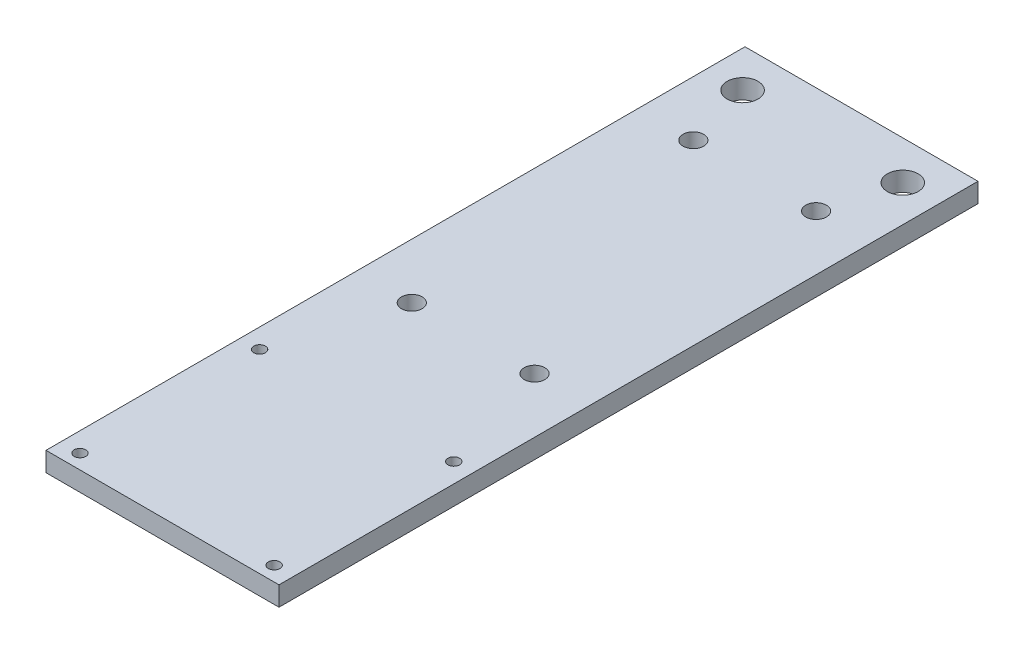
SolidWorks part; units mm, degrees
material "6061-T6 (SS)"
ref_plane "Front Plane" through (0, 0, 0) normal (0, 0, 1) x (1, 0, 0)
ref_plane "Top Plane" through (0, 0, 0) normal (0, 1, 0) x (1, 0, 0)
ref_plane "Right Plane" through (0, 0, 0) normal (1, 0, 0) x (0, 0, -1)
sketch "Plate sketch" plane through (0, 0, 0) normal (0, 1, 0) x (1, 0, 0)
  line L1 (-38.1, -114.3) -> (38.1, -114.3)
  line L2 (-38.1, -114.3) -> (-38.1, 114.3)
  line L3 (-38.1, 114.3) -> (38.1, 114.3)
  line L4 (38.1, -114.3) -> (38.1, 114.3)
  line L5 (-38.1, -114.3) -> (38.1, 114.3) construction
  line L6 (-38.1, 114.3) -> (38.1, -114.3) construction
  point P0 (0, 0)
  dimension "D1" = 228.6
  dimension "D2" = 76.2
extrude "Plate extrude" add sketch "Plate sketch" along normal blind 6.35
hole_wizard "1/4 Clearance Hole2" positions "Sketch4" profile "Sketch5" hole size "1/4" standard "ANSI Inch" end condition through all
sketch "Sketch4" plane through (0, 6.35, 0) normal (0, 1, 0) x (1, 0, 0)
  line L17 (-20.066, 79.375) -> (20.066, 79.375) construction
  line L18 (-20.066, 79.375) -> (-20.066, -12.7) construction
  line L19 (-20.066, -12.7) -> (20.066, -12.7) construction
  line L20 (20.066, 79.375) -> (20.066, -12.7) construction
  line L27 (-38.1, 114.3) -> (-38.1, -114.3) construction
  line L29 (38.1, 114.3) -> (-38.1, 114.3) construction
  point P155 (-20.066, 79.375)
  point P156 (20.066, -12.7)
  point P159 (-20.066, -12.7)
  point P160 (20.066, 79.375)
  dimension "D1" = 40.132
  dimension "D2" = 92.075
  dimension "D3" = 127
  dimension "D4" = 18.034
sketch "Sketch5" plane through (-20.066, 6.35, -79.375) normal (1, 0, 0) x (0, 0, 1)
  line L0 (0, 0) -> (0, 6.35)
  line L1 (0, 6.35) -> (3.3782, 6.35)
  line L2 (3.3782, 6.35) -> (3.3782, 0)
  line L5 (3.3782, 0) -> (0, 0)
  line L11 (0, -6.35) -> (0, 107.95) construction
  dimension "Thru Hole Dia." = 6.7564
  dimension "Thru Hole Depth" = 6.35
hole_wizard "#6 Clearance Hole1" positions "Sketch7" profile "Sketch8" hole size "#6" standard "ANSI Inch" end condition through all
sketch "Sketch7" plane through (0, 6.35, 0) normal (0, 1, 0) x (1, 0, 0)
  line L13 (0, -1000) -> (0, 49000) construction
  line L14 (-38.1, -114.3) -> (38.1, -114.3) construction
  line L18 (-31.75, -109.5375) -> (31.75, -109.5375) construction
  point P164 (-31.75, -50.8)
  point P166 (-31.75, -109.5375)
  point P210 (31.75, -50.8)
  point P212 (31.75, -109.5375)
  point P229 (0, -114.3)
  point P230 (0, -109.5375)
  point P237 (0, 0)
  dimension "D1" = 58.7375
  dimension "D3" = 63.5
  dimension "D6" = 4.7625
sketch "Sketch8" plane through (-31.75, 6.35, 50.8) normal (1, 0, 0) x (0, 0, 1)
  line L0 (0, 0) -> (0, 6.35)
  line L1 (0, 6.35) -> (1.8986, 6.35)
  line L2 (1.8986, 6.35) -> (1.8986, 0)
  line L5 (1.8986, 0) -> (0, 0)
  line L11 (0, -6.35) -> (0, 107.95) construction
  dimension "Thru Hole Dia." = 3.7973
  dimension "Thru Hole Depth" = 6.35
hole_wizard "Ø6.0mm Dowel Hole1" positions "Sketch9" profile "Sketch10" hole size "Ø6.0" standard "ANSI Metric"
sketch "Sketch9" plane through (0, 5, 0) normal (0, 1, 0) x (1, 0, 0)
  line L0 (40, 120) -> (-40, 120) construction
  line L3 (40, -120) -> (40, 120) construction
  line L4 (-40, 120) -> (-40, -120) construction
  point P0 (-34, 110)
  point P2 (34, 110)
  dimension "D1" = 10
  dimension "D2" = 10
  dimension "D3" = 6
  dimension "D4" = 6
sketch "Sketch10" plane through (-34, 5, -110) normal (1, 0, 0) x (0, 0, 1)
  line L0 (0, 0) -> (0, 5)
  line L1 (0, 5) -> (3, 5)
  line L2 (3, 5) -> (3, 0)
  line L5 (3, 0) -> (0, 0)
  line L11 (0, -6.35) -> (0, 107.95) construction
  dimension "Thru Hole Dia." = 6
  dimension "Thru Hole Depth" = 5
hole_wizard "1/4 Clearance Hole1" positions "Sketch12" profile "Sketch11" hole size "1/4" standard "ANSI Inch"
sketch "Sketch12" plane through (0, 6.35, 0) normal (0, 1, 0) x (1, 0, 0)
  line L0 (38.1, 114.3) -> (-38.1, 114.3) construction
  line L1 (-38.1, 114.3) -> (-38.1, -114.3) construction
  point P0 (0, 107.95)
  dimension "D1" = 6.35
  dimension "D2" = 38.1
sketch "Sketch11" plane through (0, 6.35, -107.95) normal (1, 0, 0) x (0, 0, 1)
  line L0 (0, 0) -> (0, 6.35)
  line L1 (0, 6.35) -> (3.3782, 6.35)
  line L2 (3.3782, 6.35) -> (3.3782, 0)
  line L5 (3.3782, 0) -> (0, 0)
  line L11 (0, -6.35) -> (0, 107.95) construction
  dimension "Thru Hole Dia." = 6.7564
  dimension "Thru Hole Depth" = 6.35
hole_wizard "3/8 Clearance Hole1" positions "Sketch13" profile "Sketch14" hole size "3/8" standard "ANSI Inch" end condition through all
sketch "Sketch13" plane through (0, 6.35, 0) normal (0, 1, 0) x (1, 0, 0)
  line L0 (-26.1937, 101.6) -> (26.1937, 101.6) construction
  line L7 (38.1, 114.3) -> (-38.1, 114.3) construction
  point P0 (-26.1937, 101.6)
  point P2 (26.1937, 101.6)
  point P64 (0, 114.3)
  point P65 (0, 101.6)
  dimension "D1" = 52.3875
  dimension "D2" = 12.7
sketch "Sketch14" plane through (-26.1937, 6.35, -101.6) normal (1, 0, 0) x (0, 0, 1)
  line L0 (0, 0) -> (0, 6.35)
  line L1 (0, 6.35) -> (5.0419, 6.35)
  line L2 (5.0419, 6.35) -> (5.0419, 0)
  line L5 (5.0419, 0) -> (0, 0)
  line L11 (0, -6.35) -> (0, 107.95) construction
  dimension "Thru Hole Dia." = 10.0838
  dimension "Thru Hole Depth" = 6.35
